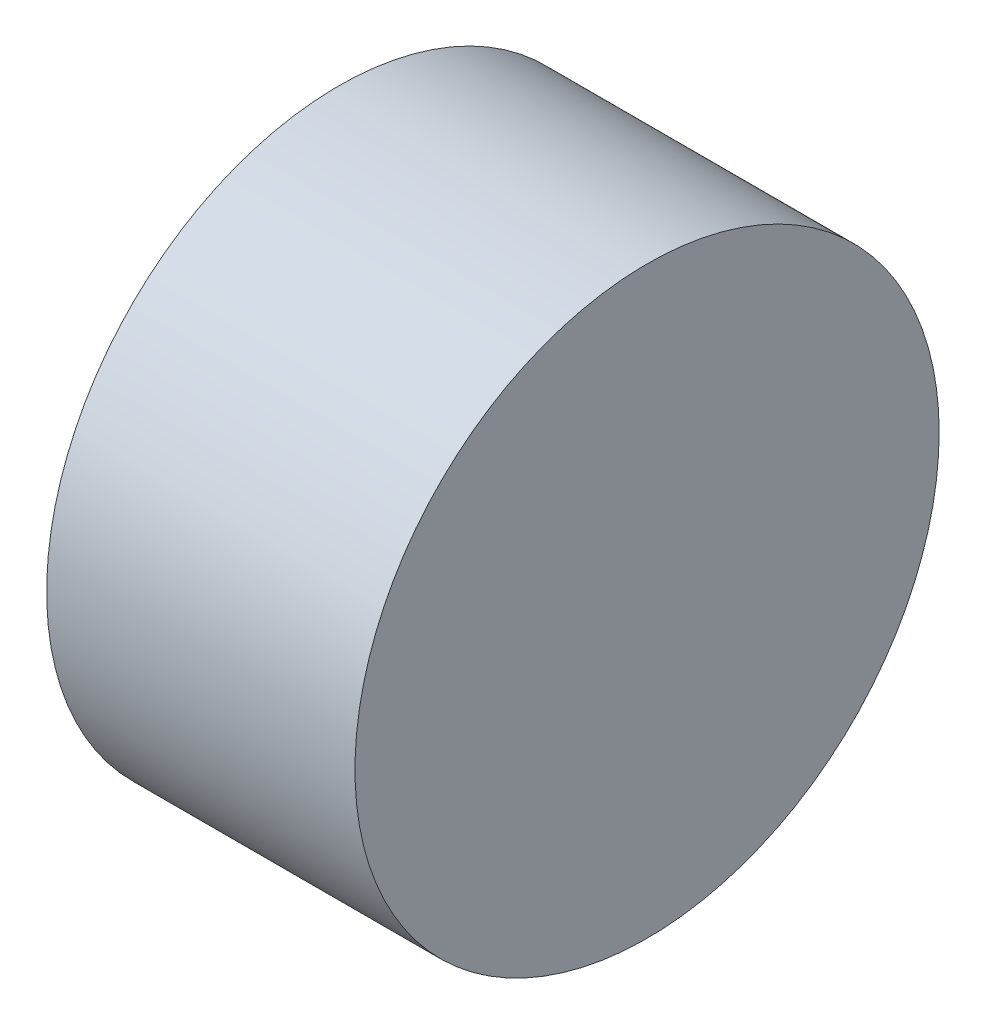
SolidWorks part; units mm, degrees
ref_plane "Front Plane" through (0, 0, 0) normal (0, 0, 1) x (1, 0, 0)
ref_plane "Top Plane" through (0, 0, 0) normal (0, 1, 0) x (1, 0, 0)
ref_plane "Right Plane" through (0, 0, 0) normal (1, 0, 0) x (0, 0, -1)
sketch "Sketch1" plane through (0, 0, 0) normal (1, 0, 0) x (0, 0, -1)
  circle A0 centre (0, 0) radius 36
extrude "Boss-Extrude1" add sketch "Sketch1" along normal blind 38
